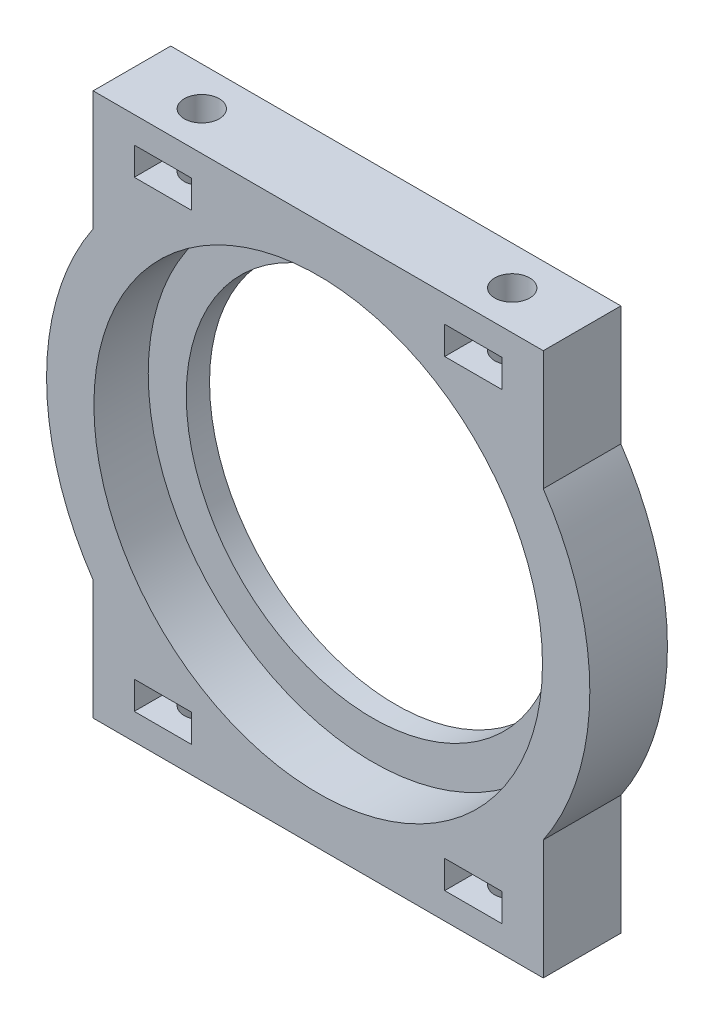
SolidWorks part; units mm, degrees
material "ABS"
ref_plane "Alzado" through (0, 0, 0) normal (0, 0, 1) x (1, 0, 0)
ref_plane "Planta" through (0, 0, 0) normal (0, 1, 0) x (1, 0, 0)
ref_plane "Vista lateral" through (0, 0, 0) normal (1, 0, 0) x (0, 0, -1)
sketch "Croquis1" plane through (0, 0, 0) normal (0, 0, 1) x (1, 0, 0)
  line L0 (-29, 19.5959) -> (-29, 35)
  line L1 (-29, -35) -> (29, -35)
  line L2 (-29, -35) -> (-29, -19.5959)
  line L3 (-29, 35) -> (29, 35)
  line L4 (29, -35) -> (29, -19.5959)
  line L5 (-29, -35) -> (29, 35) construction
  line L6 (-29, 35) -> (29, -35) construction
  line L7 (29, 19.5959) -> (29, 35)
  arc A0 (-29, 19.5959) -> (-29, -19.5959) centre (0, 0) ccw
  arc A1 (29, -19.5959) -> (29, 19.5959) centre (0, 0) ccw
  circle A2 centre (0, 0) radius 28.9
  dimension "D1" = 70
  dimension "D4" = 57.8
  dimension "D2" = 58
  dimension "D3" = 70
extrude "Saliente-Extruir1" add sketch "Croquis1" along normal mid plane 10
sketch "Croquis2" plane through (0, 0, -5) normal (0, 0, -1) x (-1, 0, 0)
  circle A0 centre (0, 0) radius 28.9 construction
  circle A1 centre (0, 0) radius 28.9
  circle A2 centre (0, 0) radius 24
  dimension "D1" = 48
extrude "Saliente-Extruir2" add sketch "Croquis2" against normal blind 3
ref_plane "Plano1" through (0, 28, 0) normal (0, 1, 0) x (1, 0, 0)
sketch "Croquis5" plane through (0, 28, 0) normal (0, 1, 0) x (1, 0, 0)
  line L0 (20, 0) -> (-20, 0) construction
  line L1 (-23.7, -2.1362) -> (-23.7, -5)
  line L2 (-23.7, 2.1362) -> (-23.7, -2.1362)
  line L3 (-23.7, -2.1362) -> (-20, -4.2724) construction
  line L4 (-20, -4.2724) -> (-16.3, -2.1362) construction
  line L5 (-16.3, -2.1362) -> (-16.3, 2.1362)
  line L6 (-16.3, 2.1362) -> (-20, 4.2724)
  line L7 (-20, 4.2724) -> (-23.7, 2.1362)
  line L8 (16.3, 2.1362) -> (16.3, -2.1362)
  line L9 (16.3, -2.1362) -> (20, -4.2724) construction
  line L10 (20, -4.2724) -> (23.7, -2.1362) construction
  line L11 (23.7, -2.1362) -> (23.7, 2.1362)
  line L12 (23.7, 2.1362) -> (20, 4.2724)
  line L13 (20, 4.2724) -> (16.3, 2.1362)
  line L14 (29, -5) -> (-29, -5) construction
  line L15 (-23.7, -5) -> (-16.3, -5)
  line L16 (-16.3, -5) -> (-16.3, -2.1362)
  line L17 (16.3, -2.1362) -> (16.3, -5)
  line L18 (16.3, -5) -> (23.7, -5)
  line L19 (23.7, -5) -> (23.7, -2.1362)
  circle A0 centre (-20, 0) radius 3.7 construction
  circle A1 centre (20, 0) radius 3.7 construction
  point P4 (0, 0)
  dimension "D1" = 7.4
  dimension "D2" = 40
extrude "Cortar-Extruir1" cut sketch "Croquis5" along normal blind 3.6
sketch "Croquis6" plane through (0, 35, 0) normal (0, 1, 0) x (1, 0, 0)
  line L0 (0, 0) -> (-16.3, 0) construction
  line L1 (-16.3, -5) -> (-16.3, 2.1362) construction
  line L2 (-16.3, 0) -> (-23.7, 0) construction
  line L3 (-23.7, 2.1362) -> (-23.7, -5) construction
  line L4 (0, -5.5) -> (0, 5.5) construction
  circle A0 centre (-20, 0) radius 2.25
  circle A1 centre (20, 0) radius 2.25
  dimension "D1" = 4.5
extrude "Cortar-Extruir2" cut sketch "Croquis6" against normal blind 10
mirror "Simetría1" about plane through (0, 0, 0) normal (0, 1, 0) of "Cortar-Extruir2", "Cortar-Extruir1"
